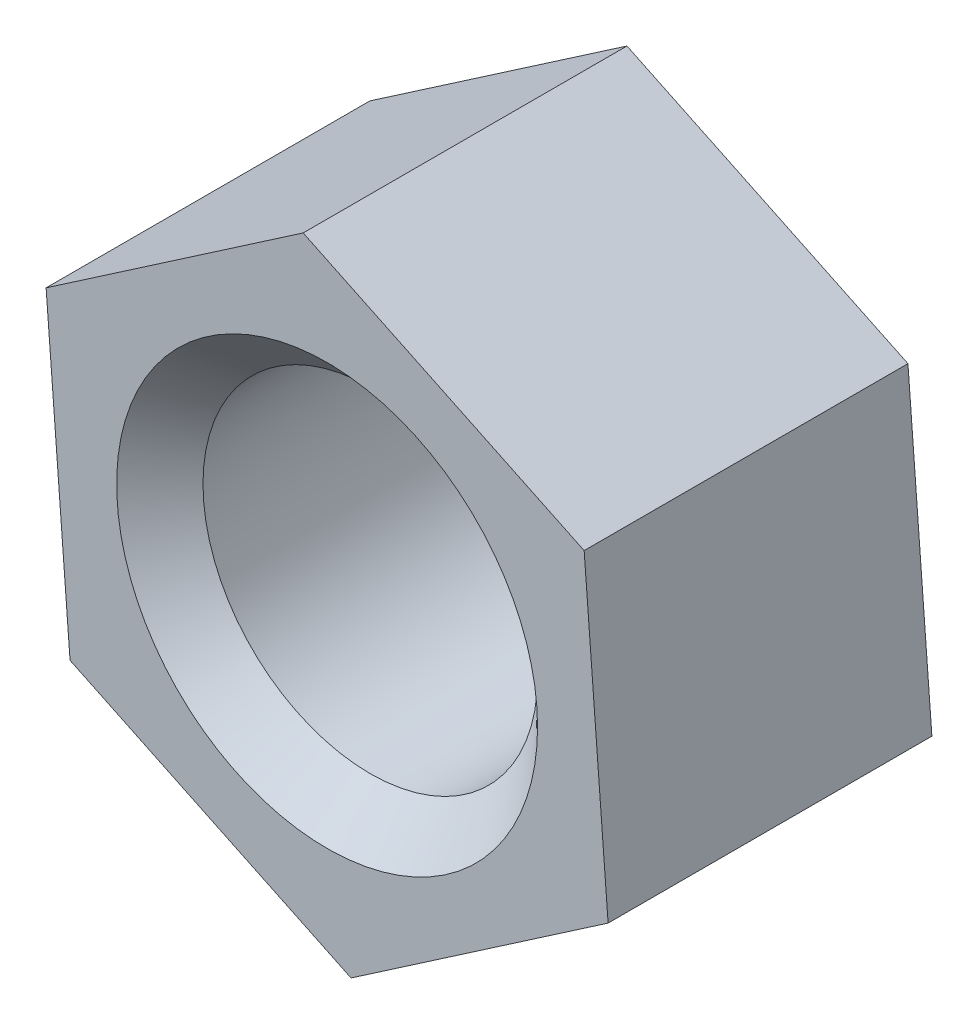
SolidWorks part; units mm, degrees
ref_plane "Front Plane" through (0, 0, 0) normal (0, 0, 1) x (1, 0, 0)
ref_plane "Top Plane" through (0, 0, 0) normal (0, 1, 0) x (1, 0, 0)
ref_plane "Right Plane" through (0, 0, 0) normal (1, 0, 0) x (0, 0, -1)
sketch "Sketch1" plane through (0, 0, 0) normal (0, 0, 1) x (1, 0, 0)
  line L1 (13.0177, -6.2348) -> (11.9083, 8.1563)
  line L2 (11.9083, 8.1563) -> (-1.1094, 14.3911)
  line L3 (-1.1094, 14.3911) -> (-13.0177, 6.2348)
  line L4 (-13.0177, 6.2348) -> (-11.9083, -8.1563)
  line L5 (-11.9083, -8.1563) -> (1.1094, -14.3911)
  line L6 (1.1094, -14.3911) -> (13.0177, -6.2348)
  circle A0 centre (0, 0) radius 12.5 construction
  dimension "D1" = 25
extrude "Boss-Extrude1" add sketch "Sketch1" along normal blind 15
sketch "Sketch2" plane through (0, 0, 0) normal (0, 0, -1) x (-1, 0, 0)
  circle A0 centre (0, 0) radius 7.75
  dimension "D1" = 15.5
extrude "Cut-Extrude1" cut sketch "Sketch2" against normal through all
chamfer "Chamfer1" distance 2 angle 45 2 edges at (-7.75, 0, 0) (-7.75, 0, 15)
